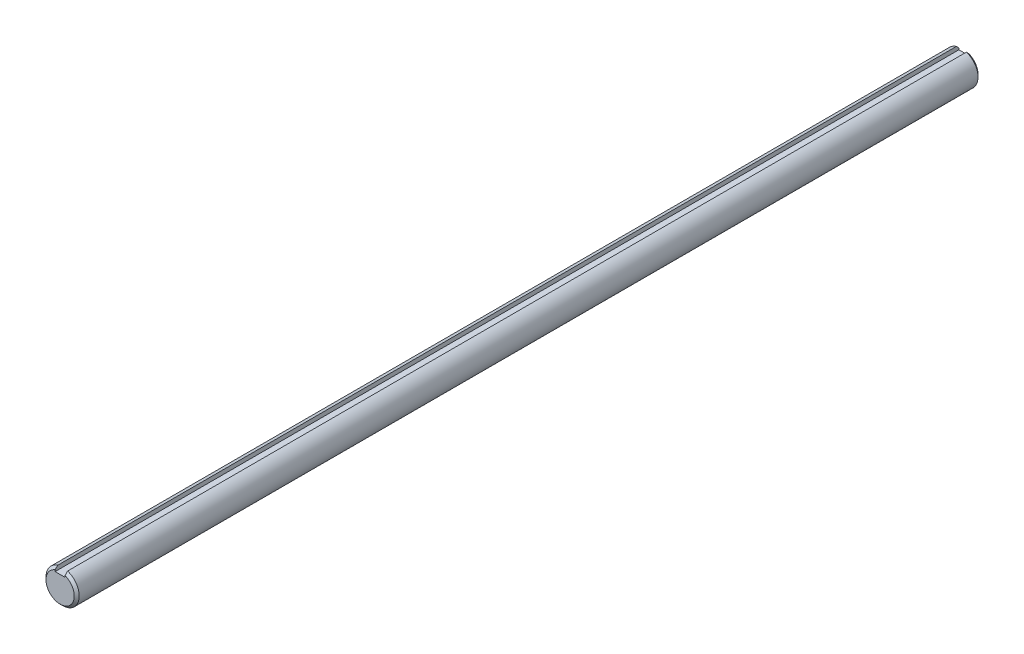
SolidWorks part; units mm, degrees
ref_plane "Front" through (0, 0, 0) normal (0, 0, 1) x (1, 0, 0)
ref_plane "Top" through (0, 0, 0) normal (0, 1, 0) x (1, 0, 0)
ref_plane "Right" through (0, 0, 0) normal (1, 0, 0) x (0, 0, -1)
sketch "Sketch1" plane through (0, 0, 0) normal (0, 0, 1) x (1, 0, 0)
  circle A0 centre (0, 0) radius 3.9688
  dimension "dia" = 7.9375
extrude "Extrude1" add sketch "Sketch1" along normal mid plane 215.9
sketch "Sketch2" plane through (0, 0, 0) normal (1, 0, 0) x (0, 0, -1)
  point P0 (-107.95, 3.9688)
  point P1 (107.95, 3.9688)
  point P2 (107.95, -3.9688)
chamfer "Chamfer1" distance 0.5953 angle 45 2 edges at (3.9688, 0, -107.95) (3.9688, 0, 107.95)
sketch "Sketch3" plane through (0, 0, 0) normal (0, 0, 1) x (1, 0, 0)
  line L1 (-1.1906, 3.9688) -> (1.1906, 3.9688)
  line L2 (-1.1906, 3.9688) -> (-1.1906, 2.7781)
  line L3 (-1.1906, 2.7781) -> (1.1906, 2.7781)
  line L4 (1.1906, 3.9688) -> (1.1906, 2.7781)
  dimension "key wd" = 2.3813
  dimension "key dp" = 1.1906
extrude "Extrude2" cut sketch "Sketch3" against normal through all and the other way through all
equation "\"D1@Chamfer1\" = \"dia@Sketch1\" * .075"
